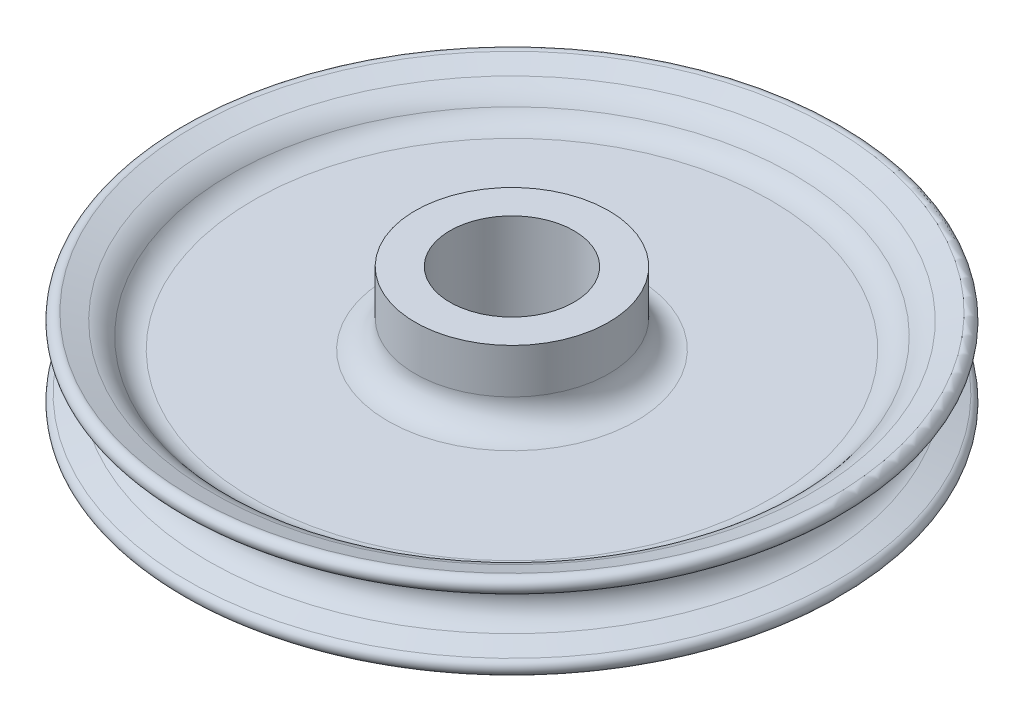
SolidWorks part; units mm, degrees
ref_plane "Front Plane" through (0, 0, 0) normal (1, 0, 0) x (0, 1, 0)
ref_plane "Top Plane" through (0, 0, 0) normal (0, 0, 1) x (0, 1, 0)
ref_plane "Right Plane" through (0, 0, 0) normal (0, 1, 0) x (-1, 0, 0)
sketch "Sketch1" plane through (0, 0, 0) normal (1, 0, 0) x (0, 1, 0)
  line L0 (-389.4129, 0) -> (384.0044, 0) construction
  line L1 (0, 251) -> (0, -388.8937) construction
  line L2 (-66, 50) -> (66, 50)
  line L3 (-66, 78) -> (-30, 78)
  line L4 (-66, 50) -> (-66, 78)
  line L5 (66, 78) -> (66, 50)
  line L6 (-8, 208.5265) -> (-8, 100)
  line L7 (8, 208.5265) -> (8, 100)
  line L8 (-24.4857, 251) -> (30, 251) construction
  line L9 (17.0352, 245.1861) -> (22.6432, 261.6179)
  line L10 (34, 257.742) -> (28.392, 241.3102)
  line L11 (-34, 257.742) -> (-28.392, 241.3102)
  line L12 (-17.0352, 245.1861) -> (-22.6432, 261.6179)
  line L13 (30, 78) -> (66, 78)
  arc A0 (-30, 78) -> (-8, 100) centre (-30, 100) ccw
  arc A1 (30, 78) -> (8, 100) centre (30, 100) cw
  arc A2 (-17.0352, 245.1861) -> (17.0352, 245.1861) centre (0, 251) ccw
  arc A3 (22.6432, 261.6179) -> (34, 257.742) centre (28.3216, 259.68) cw
  arc A4 (-28.392, 241.3102) -> (-17.3077, 226.496) centre (0, 251) ccw
  arc A5 (-22.6432, 261.6179) -> (-34, 257.742) centre (-28.3216, 259.68) ccw
  arc A6 (17.3077, 226.496) -> (28.392, 241.3102) centre (0, 251) ccw
  arc A7 (8, 208.5265) -> (17.3077, 226.496) centre (30, 208.5265) cw
  arc A8 (-8, 208.5265) -> (-17.3077, 226.496) centre (-30, 208.5265) ccw
  point P7 (0, 50)
  point P12 (-8, 100)
  point P26 (29.7801, 265.5)
  point P37 (8, 222.0863)
  dimension "D4" = 44
  dimension "D5" = 16
  dimension "D7" = 18
  dimension "D8" = 6
  dimension "D10" = 60
  dimension "D12" = 8.68
  dimension "D11" = 68
  dimension "D13" = 22
  dimension "D1" = 132
  dimension "D2" = 100
  dimension "D3" = 156
  dimension "D6" = 251
  dimension "D9" = 531
revolve "Revolve1" add sketch "Sketch1" angle 360 about L0
